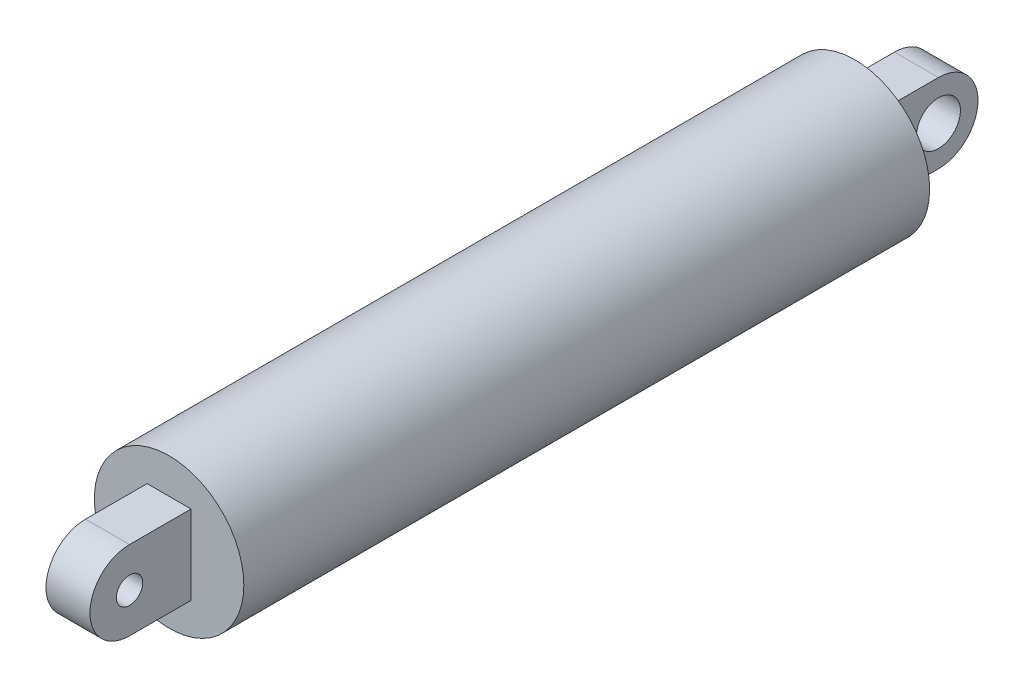
SolidWorks part; units mm, degrees
ref_plane "Front Plane" through (0, 0, 0) normal (0, 0, 1) x (1, 0, 0)
ref_plane "Top Plane" through (0, 0, 0) normal (0, 1, 0) x (1, 0, 0)
ref_plane "Right Plane" through (0, 0, 0) normal (1, 0, 0) x (0, 0, -1)
sketch "Sketch1" plane through (0, 0, 0) normal (1, 0, 0) x (0, 0, -1)
  line L0 (-27.6695, 0) -> (81.0655, 0) construction
  line L1 (0, 0) -> (0, 8.5)
  line L2 (0, 8.5) -> (78, 8.5)
  line L3 (78, 8.5) -> (78, 0)
  line L4 (0, 0) -> (78, 0)
  dimension "D1" = 17
  dimension "78" = 78
revolve "Revolve1" add sketch "Sketch1" angle 360 about L0
sketch "Sketch2" plane through (0, 0, 0) normal (1, 0, 0) x (0, 0, -1)
  line L0 (-7, 4.5) -> (0, 4.5)
  line L1 (0, 8.5) -> (0, -8.5) construction
  line L2 (-7, -4.5) -> (0, -4.5)
  line L3 (85, 4.5) -> (78, 4.5)
  line L6 (85, -4.5) -> (78, -4.5)
  line L9 (0, 4.5) -> (0, -4.5)
  line L10 (78, 4.5) -> (78, -4.5)
  line L11 (78, -8.5) -> (78, 8.5) construction
  circle A0 centre (-7, 0) radius 1.5
  arc A1 (-7, 4.5) -> (-7, -4.5) centre (-7, 0) ccw
  circle A2 centre (85, 0) radius 2.5
  arc A3 (85, -4.5) -> (85, 4.5) centre (85, 0) ccw
  dimension "D2" = 3
  dimension "D3" = 5
  dimension "D4" = 9
  dimension "D5" = 9
  dimension "D1" = 92
  dimension "D6" = 7
extrude "Boss-Extrude1" add sketch "Sketch2" along normal mid plane 5
